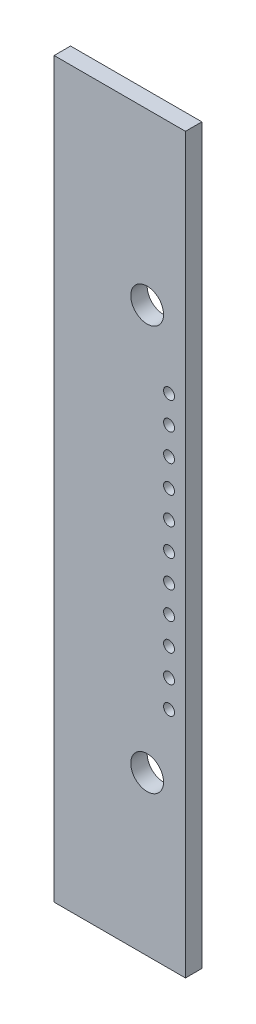
SolidWorks part; units mm, degrees
ref_plane "Front Plane" through (0, 0, 0) normal (1, 0, 0) x (0, 1, 0)
ref_plane "Top Plane" through (0, 0, 0) normal (0, 0, 1) x (0, 1, 0)
ref_plane "Right Plane" through (0, 0, 0) normal (0, 1, 0) x (-1, 0, 0)
sketch "Sketch1" plane through (0, 0, 0) normal (0, 0, 1) x (0, 1, 0)
  line L1 (-33.5, -6) -> (33.5, -6)
  line L2 (-33.5, -6) -> (-33.5, 6)
  line L3 (-33.5, 6) -> (33.5, 6)
  line L4 (33.5, -6) -> (33.5, 6)
  line L5 (-33.5, -6) -> (33.5, 6) construction
  line L6 (-33.5, 6) -> (33.5, -6) construction
  point P0 (0, 0)
  dimension "D1" = 67
  dimension "D2" = 12
extrude "Boss-Extrude1" add sketch "Sketch1" along normal mid plane 1.5
sketch "Sketch2" plane through (0, 0, 0.75) normal (0, 0, 1) x (1, 0, 0)
  line L0 (6, -33.5) -> (6, 33.5) construction
  line L1 (-6, -33.5) -> (6, -33.5) construction
  line L3 (6, 33.5) -> (-6, 33.5) construction
  circle A0 centre (4.5, -13) radius 0.5
  circle A1 centre (4.5, -10.5) radius 0.5
  circle A2 centre (4.5, -8) radius 0.5
  circle A3 centre (4.5, -5.5) radius 0.5
  circle A4 centre (4.5, -3) radius 0.5
  circle A5 centre (4.5, -0.5) radius 0.5
  circle A6 centre (4.5, 2) radius 0.5
  circle A7 centre (4.5, 4.5) radius 0.5
  circle A8 centre (4.5, 7) radius 0.5
  circle A9 centre (4.5, 9.5) radius 0.5
  circle A10 centre (4.5, 12) radius 0.5
  dimension "D1" = 1
  dimension "D2" = 1.5
  dimension "D3" = 20.5
  dimension "D4" = 11
extrude "Cut-Extrude1" cut sketch "Sketch2" against normal blind 1.5
sketch "Sketch3" plane through (0, 0, 0.75) normal (0, 0, 1) x (1, 0, 0)
  line L0 (-6, -33.5) -> (6, -33.5) construction
  line L1 (6, -33.5) -> (6, 33.5) construction
  circle A0 centre (2.5, -19) radius 1.5
  circle A1 centre (2.5, 18) radius 1.5
  dimension "D1" = 3
  dimension "D2" = 14.5
  dimension "D3" = 3.5
  dimension "D4" = 2
extrude "Cut-Extrude2" cut sketch "Sketch3" against normal blind 1.5
